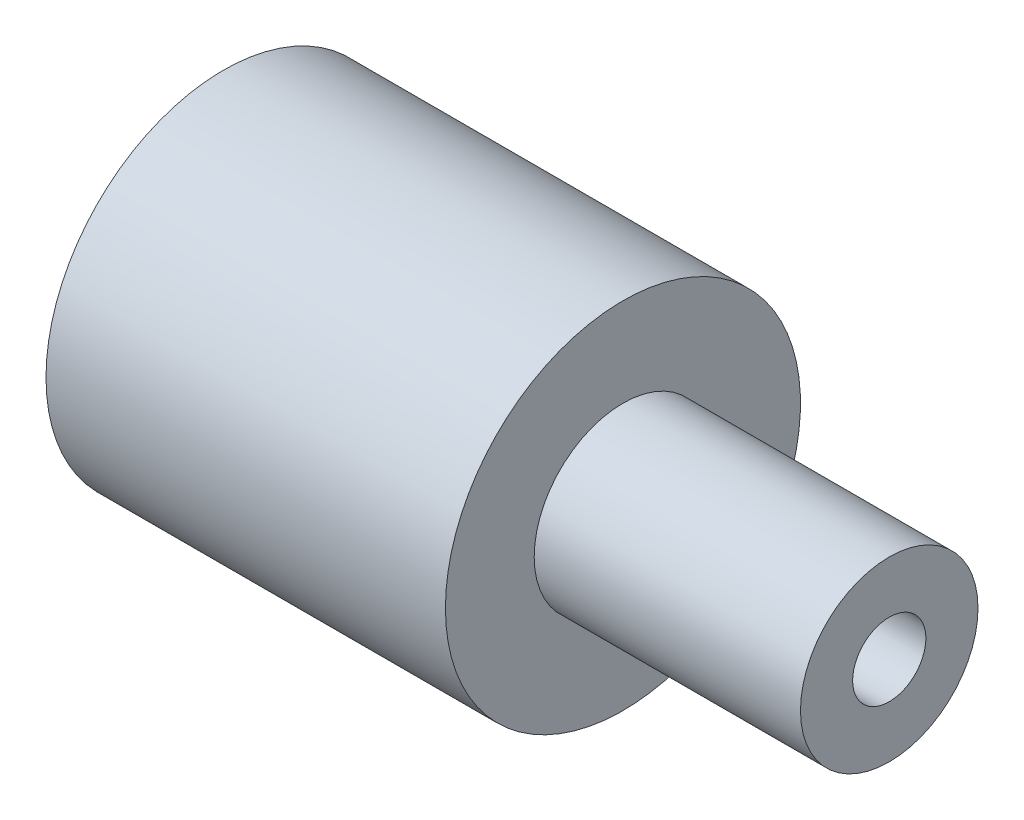
SolidWorks part; units mm, degrees
ref_plane "Plan de face" through (0, 0, 0) normal (0, 0, 1) x (1, 0, 0)
ref_plane "Plan de dessus" through (0, 0, 0) normal (0, 1, 0) x (1, 0, 0)
ref_plane "Plan de droite" through (0, 0, 0) normal (1, 0, 0) x (0, 0, -1)
sketch "Esquisse1" plane through (0, 0, 0) normal (0, 0, 1) x (1, 0, 0)
  line L0 (0, 0) -> (26.8459, 0) construction
  line L1 (0, 0) -> (0, 8)
  line L2 (0, 8) -> (18, 8)
  line L3 (18, 8) -> (18, 4)
  line L4 (18, 4) -> (30, 4)
  line L5 (30, 4) -> (30, 0)
  line L6 (30, 0) -> (0, 0)
  dimension "D1" = 16
  dimension "D2" = 8
  dimension "D3" = 12
  dimension "D4" = 30
revolve "Révolution1" add sketch "Esquisse1" angle 360 about L0
hole_wizard "Trou taraudé M41" positions "Esquisse2" profile "Esquisse3" tap size "M4" standard "ISO" end condition through all
sketch "Esquisse2" plane through (0, 0, 0) normal (-1, 0, 0) x (0, 0, 1)
  point P0 (0, 0)
cosmetic thread "Filetage de perçage1" parameters "D2"=4
sketch "Esquisse3" plane through (0, 0, 0) normal (0, 1, 0) x (0, 0, 1)
  line L0 (0, 0) -> (0, 30)
  line L1 (0, 30) -> (1.65, 30)
  line L2 (1.65, 30) -> (1.65, 0)
  line L5 (1.65, 0) -> (0, 0)
  line L11 (0, -6.35) -> (0, 107.95) construction
  dimension "Diamètre du trou pour taraudage jusqu'au prochain" = 3.3
  dimension "Profondeur du trou pour taraudage jusqu'au prochain" = 30
